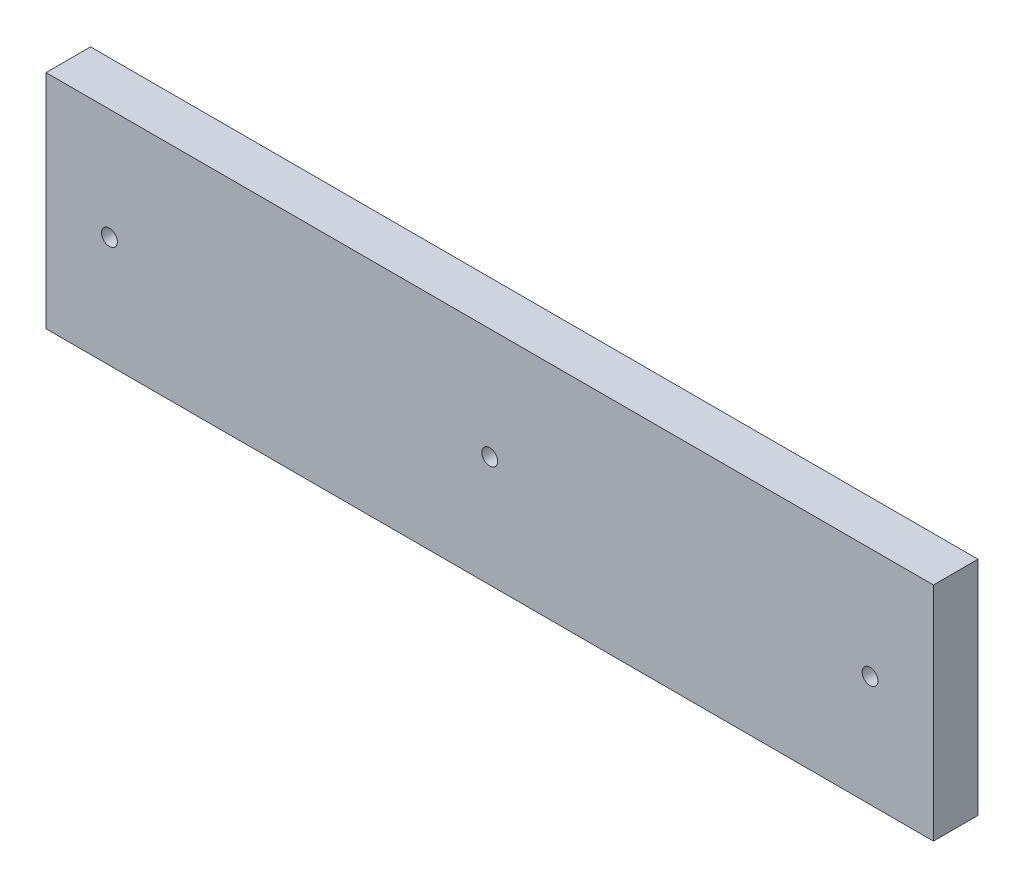
SolidWorks part; units mm, degrees
ref_plane "Front Plane" through (0, 0, 0) normal (0, 0, 1) x (1, 0, 0)
ref_plane "Top Plane" through (0, 0, 0) normal (0, 1, 0) x (1, 0, 0)
ref_plane "Right Plane" through (0, 0, 0) normal (1, 0, 0) x (0, 0, -1)
sketch "Sketch1" plane through (0, 0, 0) normal (0, 0, 1) x (1, 0, 0)
  line L0 (-203.2, 0) -> (0, 0) construction
  line L1 (254, 44.45) -> (-254, 44.45)
  line L2 (254, 44.45) -> (254, -44.45)
  line L3 (254, -44.45) -> (-254, -44.45)
  line L4 (-254, 44.45) -> (-254, -44.45)
  line L5 (254, 44.45) -> (-254, -44.45) construction
  line L6 (254, -44.45) -> (-254, 44.45) construction
  line L7 (0, 0) -> (203.2, 0) construction
  circle A0 centre (203.2, 0) radius 3.175
  circle A1 centre (0, 0) radius 3.175
  circle A2 centre (-203.2, 0) radius 3.175
  point P0 (0, 0)
  dimension "D3" = 6.35
  dimension "D1" = 508
  dimension "D2" = 88.9
  dimension "D4" = 203.2
extrude "Boss-Extrude1" [suppressed] add sketch "Sketch1" along normal blind 17.8562
sketch "Sketch2" plane through (0, 0, 0) normal (0, 0, 1) x (1, 0, 0)
  line L0 (-152.4, 0) -> (0, 0) construction
  line L1 (177.8, 44.45) -> (-177.8, 44.45)
  line L2 (177.8, 44.45) -> (177.8, -44.45)
  line L3 (177.8, -44.45) -> (-177.8, -44.45)
  line L4 (-177.8, 44.45) -> (-177.8, -44.45)
  line L5 (177.8, 44.45) -> (-177.8, -44.45) construction
  line L6 (177.8, -44.45) -> (-177.8, 44.45) construction
  line L7 (0, 0) -> (152.4, 0) construction
  circle A0 centre (-152.4, 0) radius 3.175
  circle A1 centre (0, 0) radius 3.175
  circle A2 centre (152.4, 0) radius 3.175
  point P0 (0, 0)
  dimension "D4" = 6.35
  dimension "D1" = 88.9
  dimension "D2" = 355.6
  dimension "D3" = 152.4
extrude "Boss-Extrude2" add sketch "Sketch2" along normal blind 17.8562
